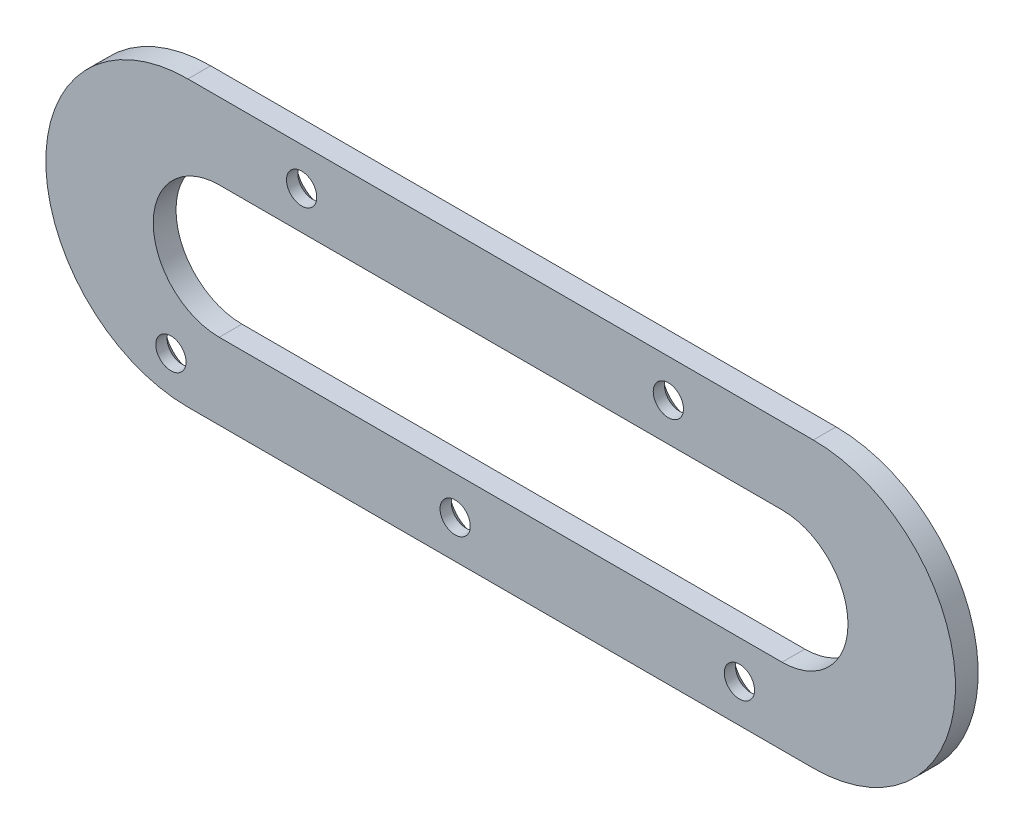
SolidWorks part; units mm, degrees
ref_plane "Front Plane" through (0, 0, 0) normal (0, 0, 1) x (1, 0, 0)
ref_plane "Top Plane" through (0, 0, 0) normal (0, 1, 0) x (1, 0, 0)
ref_plane "Right Plane" through (0, 0, 0) normal (1, 0, 0) x (0, 0, -1)
sketch "Sketch1" plane through (0, 0, 0) normal (0, 0, 1) x (1, 0, 0)
  line L3 (-95.25, -16.8817) -> (-234.95, -16.8817) construction
  line L4 (-95.25, -48.6317) -> (-234.95, -48.6317)
  line L5 (-95.25, 14.8683) -> (-234.95, 14.8683)
  arc A2 (-95.25, -48.6317) -> (-95.25, 14.8683) centre (-95.25, -16.8817) ccw
  arc A3 (-234.95, 14.8683) -> (-234.95, -48.6317) centre (-234.95, -16.8817) ccw
  point P12 (-165.1, -16.8817)
  dimension "D2" = 139.7
  dimension "D1" = 63.5
extrude "Boss-Extrude2" add sketch "Sketch1" along normal blind 5.08
sketch "Sketch2" plane through (0, 0, 0) normal (0, 0, -1) x (-1, 0, 0)
  line L0 (63.5, -16.8817) -> (266.7, -16.8817) construction
  line L1 (165.1, 14.8683) -> (165.1, -48.6317) construction
  line L2 (95.25, 14.8683) -> (234.95, 14.8683) construction
  line L3 (234.95, -48.6317) -> (95.25, -48.6317) construction
  line L4 (227.965, -16.8817) -> (102.235, -16.8817) construction
  line L5 (227.965, -31.6137) -> (102.235, -31.6137)
  line L6 (227.965, -2.1497) -> (102.235, -2.1497)
  arc A0 (95.25, 14.8683) -> (95.25, -48.6317) centre (95.25, -16.8817) ccw construction
  arc A1 (234.95, -48.6317) -> (234.95, 14.8683) centre (234.95, -16.8817) ccw construction
  arc A2 (227.965, -31.6137) -> (227.965, -2.1497) centre (227.965, -16.8817) ccw
  arc A3 (102.235, -2.1497) -> (102.235, -31.6137) centre (102.235, -16.8817) ccw
  point P16 (165.1, -16.8817)
  dimension "D2" = 125.73
  dimension "D1" = 29.464
extrude "Cut-Extrude1" cut sketch "Sketch2" against normal blind 38.862
sketch "Sketch5" plane through (0, 0, 0) normal (0, 0, -1) x (-1, 0, 0)
  line L0 (95.25, 14.8683) -> (234.95, 14.8683) construction
  line L1 (102.235, -31.6137) -> (227.965, -31.6137) construction
  circle A5 centre (238.76, -40.1227) radius 3.175
  circle A10 centre (127.635, 6.3593) radius 3.175
  arc A12 (102.235, -2.1497) -> (102.235, -31.6137) centre (102.235, -16.8817) ccw construction
  circle A13 centre (209.55, 6.3593) radius 3.175
  arc A14 (234.95, -48.6317) -> (234.95, 14.8683) centre (234.95, -16.8817) ccw construction
  circle A15 centre (111.76, -40.1227) radius 3.175
  circle A16 centre (175.26, -40.1227) radius 3.175
  point P23 (0, 0)
  dimension "D1" = 25.4
  dimension "D3" = 47.625
  dimension "D7" = 8.509
  dimension "D2" = 25.4
  dimension "D5" = 63.5
  dimension "D6" = 8.509
  dimension "D8" = 8.509
  dimension "D4" = 63.5
hole_wizard "CSK for 1/4 Flat Head Machine Screw (100)2" positions "3DSketch2" profile "Sketch8" countersink size "1/4" standard "ANSI Inch" end condition through all
sketch3d "3DSketch2"
  point P0 (-127.635, 6.3593, 0)
  point P3 (-209.55, 6.3593, 0)
sketch "Sketch8" plane through (-127.635, 6.3593, 0) normal (1, 0, 0) x (0, 1, 0)
  line L0 (0, 0) -> (0, 5.08)
  line L1 (0, 5.08) -> (3.3782, 5.08)
  line L2 (3.3782, 5.08) -> (3.3782, 2.5682)
  line L3 (3.3782, 2.5682) -> (6.4389, 0)
  line L5 (6.4389, 0) -> (0, 0)
  line L6 (-3.3782, 2.5682) -> (-6.4389, 0) construction
  line L11 (0, -6.35) -> (0, 107.95) construction
  dimension "Thru Hole Dia." = 6.7564
  dimension "Thru Hole Depth" = 5.08
  dimension "Near C'Sink Dia." = 12.8778
  dimension "Near C'Sink Angle" = 100
hole_wizard "CSK for 1/4 Flat Head Machine Screw (100)3" positions "3DSketch3" profile "Sketch9" countersink size "1/4" standard "ANSI Inch" end condition through all
sketch3d "3DSketch3"
  point P0 (-111.76, -40.1227, 0)
  point P3 (-175.26, -40.1227, 0)
sketch "Sketch9" plane through (-111.76, -40.1227, 0) normal (1, 0, 0) x (0, 1, 0)
  line L0 (0, 0) -> (0, 5.08)
  line L1 (0, 5.08) -> (3.3782, 5.08)
  line L2 (3.3782, 5.08) -> (3.3782, 2.5682)
  line L3 (3.3782, 2.5682) -> (6.4389, 0)
  line L5 (6.4389, 0) -> (0, 0)
  line L6 (-3.3782, 2.5682) -> (-6.4389, 0) construction
  line L11 (0, -6.35) -> (0, 107.95) construction
  dimension "Thru Hole Dia." = 6.7564
  dimension "Thru Hole Depth" = 5.08
  dimension "Near C'Sink Dia." = 12.8778
  dimension "Near C'Sink Angle" = 100
hole_wizard "CSK for 1/4 Flat Head Machine Screw (100)4" positions "3DSketch4" profile "Sketch10" countersink size "1/4" standard "ANSI Inch" end condition through all
sketch3d "3DSketch4"
  point P0 (-238.76, -40.1227, 0)
sketch "Sketch10" plane through (-238.76, -40.1227, 0) normal (1, 0, 0) x (0, 1, 0)
  line L0 (0, 0) -> (0, 5.08)
  line L1 (0, 5.08) -> (3.3782, 5.08)
  line L2 (3.3782, 5.08) -> (3.3782, 2.5682)
  line L3 (3.3782, 2.5682) -> (6.4389, 0)
  line L5 (6.4389, 0) -> (0, 0)
  line L6 (-3.3782, 2.5682) -> (-6.4389, 0) construction
  line L11 (0, -6.35) -> (0, 107.95) construction
  dimension "Thru Hole Dia." = 6.7564
  dimension "Thru Hole Depth" = 5.08
  dimension "Near C'Sink Dia." = 12.8778
  dimension "Near C'Sink Angle" = 100
